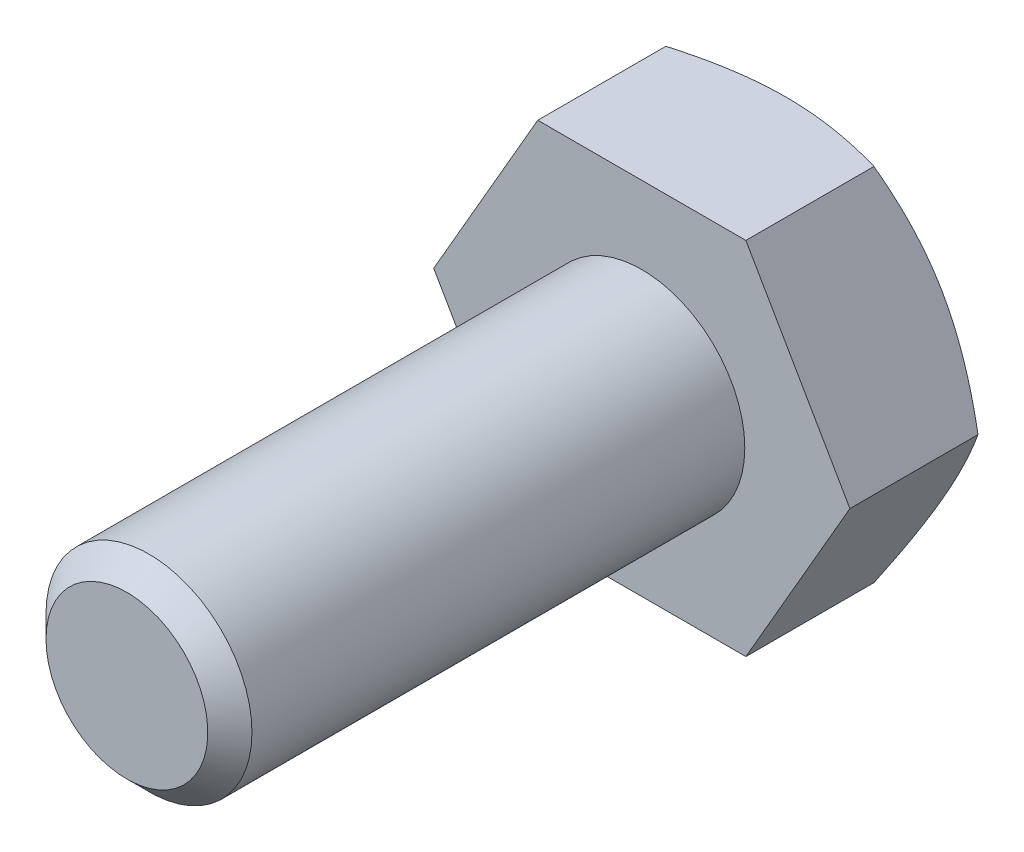
SolidWorks part; units mm, degrees
material "Plain Carbon Steel"
ref_plane "Front Plane" through (0, 0, 0) normal (0, 0, 1) x (1, 0, 0)
ref_plane "Top Plane" through (0, 0, 0) normal (0, 1, 0) x (1, 0, 0)
ref_plane "Right Plane" through (0, 0, 0) normal (1, 0, 0) x (0, 0, -1)
sketch "Sketch1" plane through (0, 0, 0) normal (0, 0, 1) x (1, 0, 0)
  line L1 (4.0415, 0) -> (2.0207, 3.5)
  line L2 (2.0207, 3.5) -> (-2.0207, 3.5)
  line L3 (-2.0207, 3.5) -> (-4.0415, 0)
  line L4 (-4.0415, 0) -> (-2.0207, -3.5)
  line L5 (-2.0207, -3.5) -> (2.0207, -3.5)
  line L6 (2.0207, -3.5) -> (4.0415, 0)
  circle A0 centre (0, 0) radius 3.5 construction
  dimension "D1" = 7
extrude "Extrude1" add sketch "Sketch1" along normal blind 2.8
sketch "Sketch2" plane through (0, 0, 2.8) normal (0, 0, 1) x (1, 0, 0)
  circle A0 centre (0, 0) radius 2
  dimension "D1" = 4
extrude "Extrude2" add sketch "Sketch2" along normal blind 10
cosmetic thread "Cosmetic Thread1" parameters "D2"=3.142
sketch "Sketch3" plane through (0, 0, 0) normal (1, 0, 0) x (0, 0, -1)
  line L0 (0, 3.5) -> (0, 103.5)
  line L1 (0, 103.5) -> (-57.735, 103.5)
  line L2 (-57.735, 103.5) -> (0, 3.5)
  line L3 (0, 0) -> (11.4679, 0) construction
  dimension "D1" = 30
  dimension "D2" = 100
revolve "Cut-Revolve1" cut sketch "Sketch3" angle 360 about L3
chamfer "Chamfer1" distance 0.429 angle 45 1 edges at (2, 0, 12.8)
